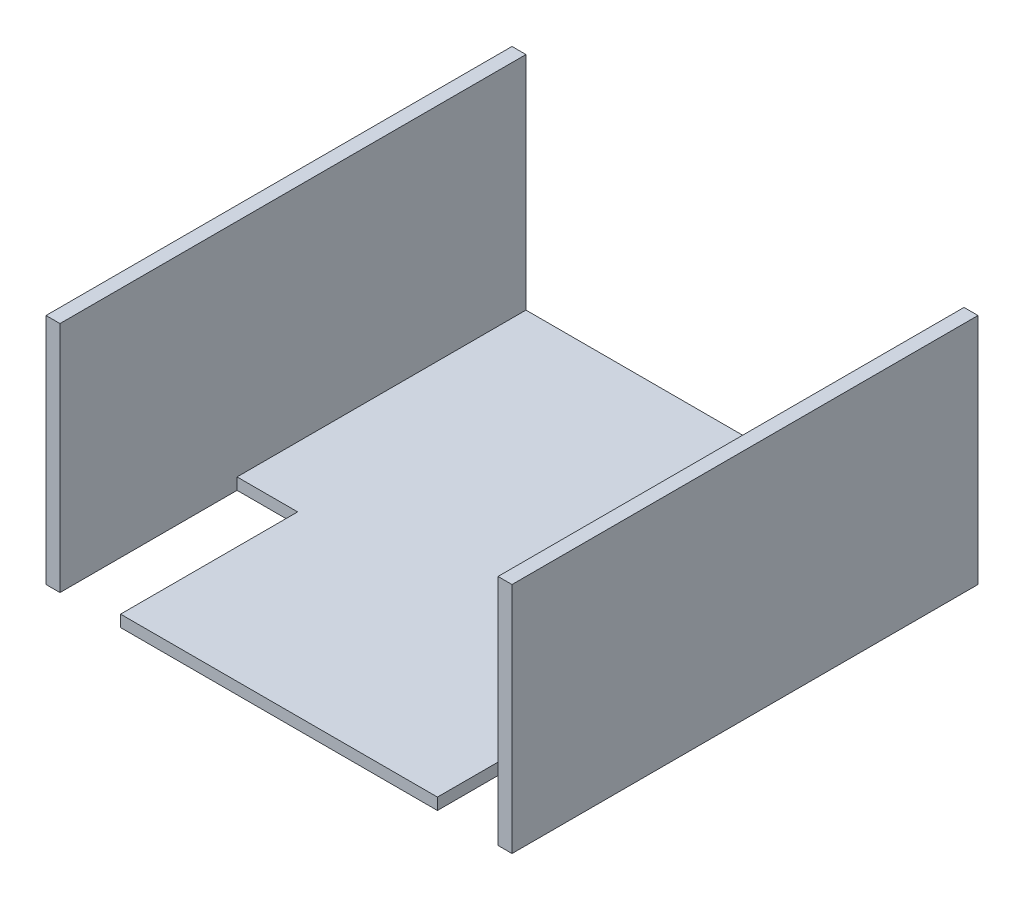
SolidWorks part; units mm, degrees
ref_plane "Alzado" through (0, 0, 0) normal (0, 0, 1) x (1, 0, 0)
ref_plane "Planta" through (0, 0, 0) normal (0, 1, 0) x (1, 0, 0)
ref_plane "Vista lateral" through (0, 0, 0) normal (1, 0, 0) x (0, 0, -1)
sketch "Croquis1" plane through (0, 0, 0) normal (0, 0, 1) x (1, 0, 0)
  line L0 (50, 0) -> (-50, 0)
  line L1 (-50, 0) -> (-50, 50)
  line L2 (-50, 50) -> (-47, 50)
  line L3 (-47, 50) -> (-47, 2.5)
  line L4 (-47, 2.5) -> (47, 2.5)
  line L5 (0, 2.5) -> (0, 0)
  line L6 (0, 0) -> (0, 13.9963) construction
  line L7 (47, 50) -> (47, 2.5)
  line L8 (50, 50) -> (47, 50)
  line L9 (50, 0) -> (50, 50)
  dimension "D1" = 50
  dimension "D2" = 50
  dimension "D3" = 3
  dimension "D4" = 2.5
extrude "Saliente-Extruir1" add sketch "Croquis1" against normal blind 100 contours L4 L7 L8 L9 L0 L1 L2 L3
sketch "Croquis2" plane through (0, 2.5, 0) normal (0, 1, 0) x (1, 0, 0)
  line L0 (0, 0) -> (0, 100) construction
  line L1 (-47, 0) -> (-34, 0)
  line L2 (-47, 0) -> (-47, 38)
  line L3 (-47, 38) -> (-34, 38)
  line L4 (-34, 0) -> (-34, 38)
  line L5 (-47, 100) -> (47, 100) construction
  line L6 (47, 38) -> (34, 38)
  line L7 (34, 0) -> (34, 38)
  line L8 (47, 0) -> (34, 0)
  line L9 (47, 0) -> (47, 38)
  dimension "D1" = 13
  dimension "D2" = 38
extrude "Cortar-Extruir2" cut sketch "Croquis2" against normal blind 10
ref_plane "Plano1" through (0, 2.5, 0) normal (0, 1, 0) x (1, 0, 0)
